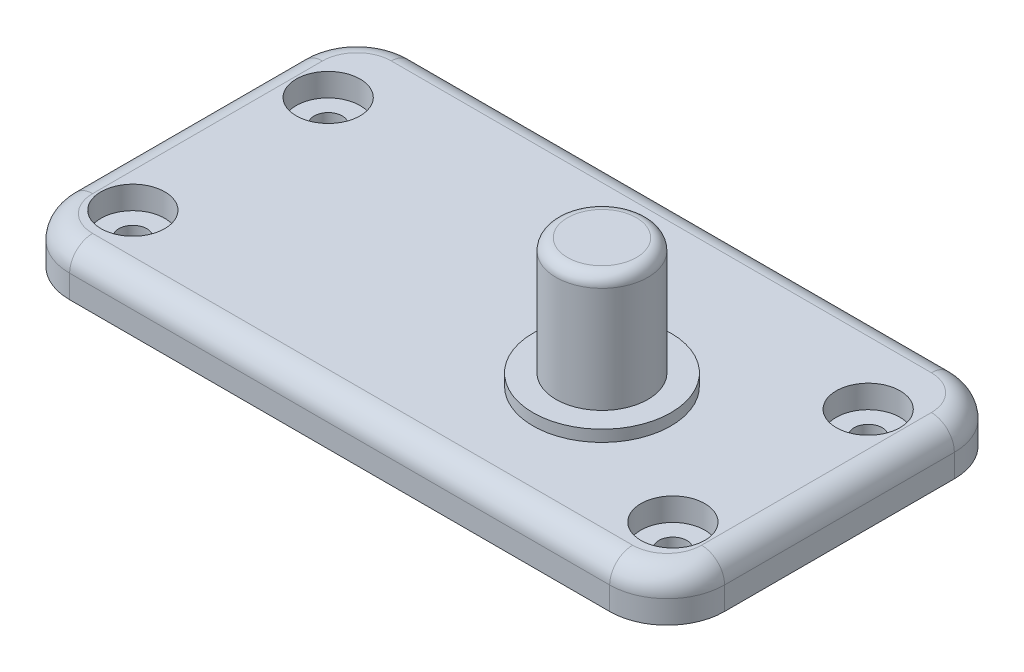
SolidWorks part; units mm, degrees
material "ABS"
ref_plane "Front" through (0, 0, 0) normal (0, 0, 1) x (1, 0, 0)
ref_plane "Top" through (0, 0, 0) normal (0, 1, 0) x (1, 0, 0)
ref_plane "Right" through (0, 0, 0) normal (1, 0, 0) x (0, 0, -1)
sketch "Sketch1" plane through (0, 0, 0) normal (0, 1, 0) x (1, 0, 0)
  line L1 (-28.5, -15) -> (28.5, -15)
  line L2 (-28.5, -15) -> (-28.5, 15)
  line L3 (-28.5, 15) -> (28.5, 15)
  line L4 (28.5, -15) -> (28.5, 15)
  point P4 (0, -15)
  point P6 (-28.5, 0)
  dimension "D1" = 57
  dimension "D2" = 30
extrude "Boss-Extrude1" add sketch "Sketch1" along normal blind 4
sketch "Sketch3" plane through (0, 4, 0) normal (0, 1, 0) x (1, 0, 0)
  line L0 (28.5, -15) -> (28.5, 15) construction
  circle A0 centre (10.18, -2.35) radius 4
  point P5 (28.5, 0)
  dimension "D1" = 8
  dimension "D2" = 18.32
  dimension "D3" = 2.35
extrude "Boss-Extrude2" add sketch "Sketch3" along normal blind 11.2
sketch "Sketch4" plane through (0, 4, 0) normal (0, 1, 0) x (1, 0, 0)
  circle A0 centre (10.18, -2.35) radius 6
  dimension "D1" = 12
extrude "Boss-Extrude3" add sketch "Sketch4" along normal blind 1
hole_wizard "CBORE for #2 Binding Head Machine Screw1" positions "Sketch5" profile "Sketch6" counterbore size "#2" standard "ANSI Inch" end condition through all
sketch "Sketch5" plane through (0, 4, 0) normal (0, 1, 0) x (1, 0, 0)
  line L0 (-23.5, -9.5) -> (23.5, -9.5) construction
  line L1 (23.5, -9.5) -> (23.5, 7.5) construction
  line L2 (23.5, 7.5) -> (-23.5, 7.5) construction
  line L3 (-23.5, 7.5) -> (-23.5, -9.5) construction
  line L5 (-28.5, 15) -> (-28.5, -15) construction
  line L6 (28.5, 15) -> (-28.5, 15) construction
  line L7 (-28.5, -15) -> (28.5, -15) construction
  point P0 (-23.5, 7.5)
  point P2 (-23.5, -9.5)
  point P4 (23.5, -9.5)
  point P6 (23.5, 7.5)
  point P24 (0, 7.5)
  point P27 (0, 15)
  dimension "D1" = 5
  dimension "D2" = 17
  dimension "D3" = 5.5
sketch "Sketch6" plane through (-23.5, 4, -7.5) normal (1, 0, 0) x (0, 0, 1)
  line L0 (0, 0) -> (0, 4)
  line L1 (0, 4) -> (1.2192, 4)
  line L3 (1.2192, 4) -> (1.2192, 2)
  line L4 (1.2192, 2) -> (2.7788, 2)
  line L5 (2.7788, 2) -> (2.7788, 0)
  line L7 (2.7788, 0) -> (0, 0)
  line L11 (0, -6.35) -> (0, 107.95) construction
  dimension "Thru Hole Dia." = 2.4384
  dimension "Thru Hole Depth" = 4
  dimension "C'Bore Dia." = 5.5575
  dimension "C'Bore Depth" = 2
fillet "Fillet1" radius 5 4 edges at (28.5, 2, -15) (28.5, 2, 15) (-28.5, 2, -15) (-28.5, 2, 15)
fillet "Fillet2" radius 2 8 edges at (27.0355, 4, 13.5355) (0, 4, 15) (-27.0355, 4, 13.5355) (-28.5, 4, 0) (-27.0355, 4, -13.5355) (0, 4, -15) (27.0355, 4, -13.5355) (28.5, 4, 0)
fillet "Fillet3" radius 1 1 edges at (10.18, 15.2, 6.35)
